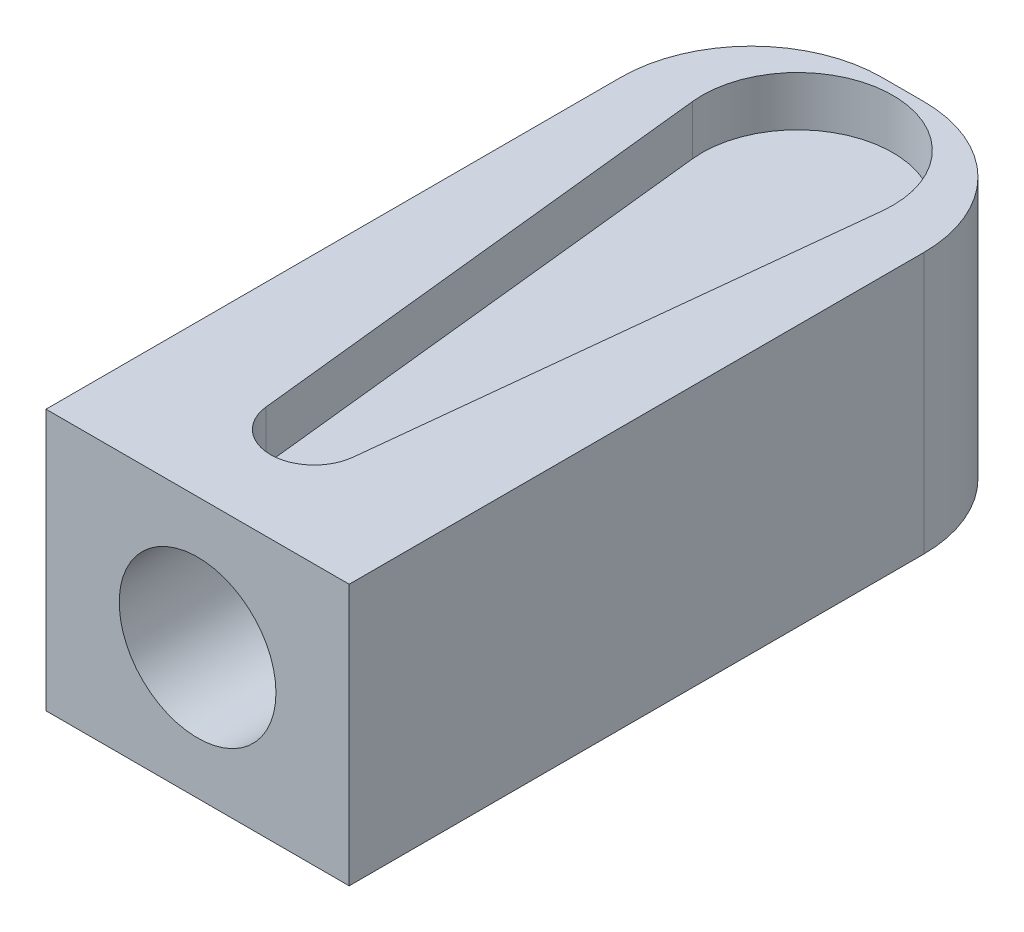
SolidWorks part; units mm, degrees
ref_plane "Front Plane" through (0, 0, 0) normal (0, 0, 1) x (1, 0, 0)
ref_plane "Top Plane" through (0, 0, 0) normal (0, 1, 0) x (1, 0, 0)
ref_plane "Right Plane" through (0, 0, 0) normal (1, 0, 0) x (0, 0, -1)
sketch "Sketch1" plane through (0, 0, 0) normal (0, 0, 1) x (1, 0, 0)
  line L1 (-5.803, -5) -> (5.803, -5)
  line L2 (-5.803, -5) -> (-5.803, 5)
  line L3 (-5.803, 5) -> (5.803, 5)
  line L4 (5.803, -5) -> (5.803, 5)
  line L5 (-5.803, -5) -> (5.803, 5) construction
  line L6 (-5.803, 5) -> (5.803, -5) construction
  circle A0 centre (0, 0) radius 3
  dimension "D1" = 6
  dimension "D2" = 10
extrude "Boss-Extrude1" add sketch "Sketch1" along normal blind 25
sketch "Sketch2" plane through (0, 0, 0) normal (0, 0, -1) x (-1, 0, 0)
  line L4 (-5.803, 5) -> (-5.803, -5)
  line L5 (-5.803, -5) -> (5.803, -5)
  line L6 (5.803, -5) -> (5.803, 5)
  line L7 (5.803, 5) -> (-5.803, 5)
  line L8 (-5.803, 5) -> (-5.803, -5)
  line L9 (-5.803, -5) -> (5.803, -5)
  line L10 (5.803, -5) -> (5.803, 5)
  line L11 (5.803, 5) -> (-5.803, 5)
  dimension "D1" = 0
extrude "Boss-Extrude2" add sketch "Sketch2" along normal blind 2
fillet "Fillet1" radius 5 2 edges at (-5.803, 0, -2) (5.803, 0, -2)
sketch "Sketch3" plane through (0, 5, 0) normal (0, 1, 0) x (1, 0, 0)
  line L0 (3.6291, -2.4248) -> (1.6654, -20.714)
  line L1 (-3.6291, -2.4248) -> (-1.6654, -20.714)
  line L2 (0, -2.0352) -> (0, -20.5352) construction
  line L3 (0, 0) -> (0, -2.0352) construction
  arc A0 (3.6291, -2.4248) -> (-3.6291, -2.4248) centre (0, -2.0352) ccw
  arc A1 (-1.6654, -20.714) -> (1.6654, -20.714) centre (0, -20.5352) ccw
  point P9 (0, 0)
  dimension "D1" = 7.3
  dimension "D2" = 3.35
  dimension "D3" = 18.5
  dimension "D4" = 2.0352
extrude "Cut-Extrude1" cut sketch "Sketch3" against normal blind 1.9
